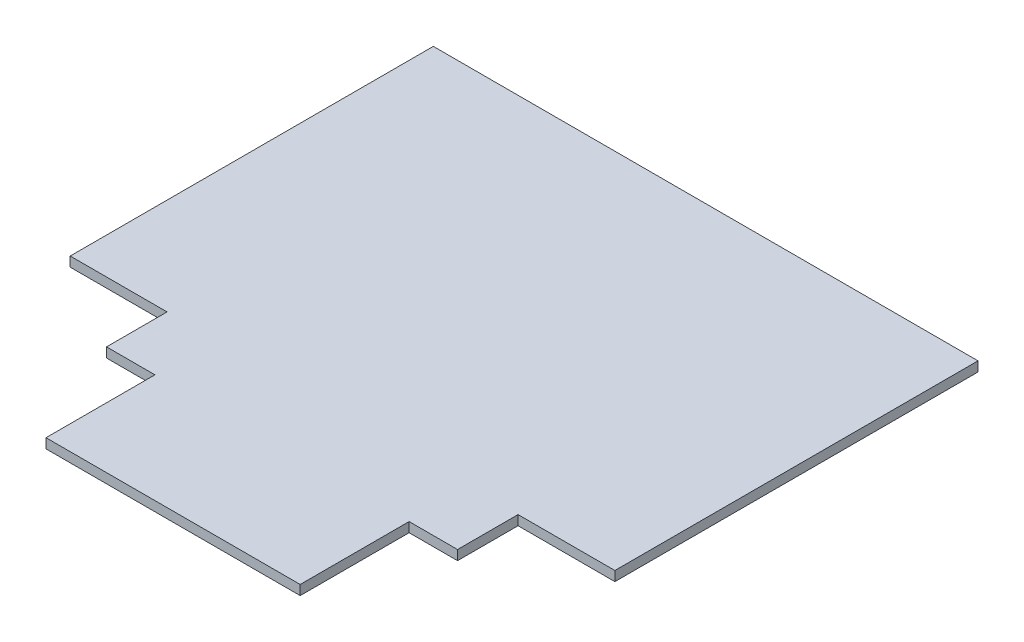
SolidWorks part; units mm, degrees
ref_plane "Front Plane" through (0, 0, 0) normal (0, 0, 1) x (1, 0, 0)
ref_plane "Top Plane" through (0, 0, 0) normal (0, 1, 0) x (1, 0, 0)
ref_plane "Right Plane" through (0, 0, 0) normal (1, 0, 0) x (0, 0, -1)
sketch "Sketch1" plane through (0, 0, 0) normal (0, 1, 0) x (1, 0, 0)
  line L1 (0, 0) -> (225, 0)
  line L2 (0, 0) -> (0, 220)
  line L3 (0, 220) -> (225, 220)
  line L4 (225, 0) -> (225, 220)
  line L5 (0, 0) -> (40, 0)
  line L6 (0, 0) -> (0, 70)
  line L7 (0, 70) -> (40, 70)
  line L8 (40, 0) -> (40, 70)
  line L9 (225, 0) -> (185, 0)
  line L10 (225, 0) -> (225, 70)
  line L11 (225, 70) -> (185, 70)
  line L12 (185, 0) -> (185, 70)
  line L13 (40, 45) -> (60, 45)
  line L14 (40, 45) -> (40, 25)
  line L15 (40, 25) -> (60, 25)
  line L16 (60, 45) -> (60, 25)
  line L17 (185, 25) -> (165, 25)
  line L18 (185, 25) -> (185, 45)
  line L19 (185, 45) -> (165, 45)
  line L20 (165, 25) -> (165, 45)
  line L21 (60, 25) -> (40, 25)
  line L22 (60, 25) -> (60, 0)
  line L23 (60, 0) -> (40, 0)
  line L24 (40, 25) -> (40, 0)
  line L25 (165, 25) -> (185, 25)
  line L26 (165, 25) -> (165, 0)
  line L27 (165, 0) -> (185, 0)
  line L28 (185, 25) -> (185, 0)
  dimension "D1" = 225
  dimension "D2" = 220
  dimension "D3" = 70
  dimension "D4" = 70
  dimension "D5" = 40
  dimension "D6" = 40
  dimension "D7" = 20
  dimension "D8" = 20
  dimension "D9" = 20
  dimension "D10" = 20
  dimension "D11" = 25
  dimension "D12" = 25
extrude "Boss-Extrude1" add sketch "Sketch1" along normal blind 4 contours L17 L20 L19 L12 L11 L4 L3 L2 L7 L8 L13 L16 L15 L1
